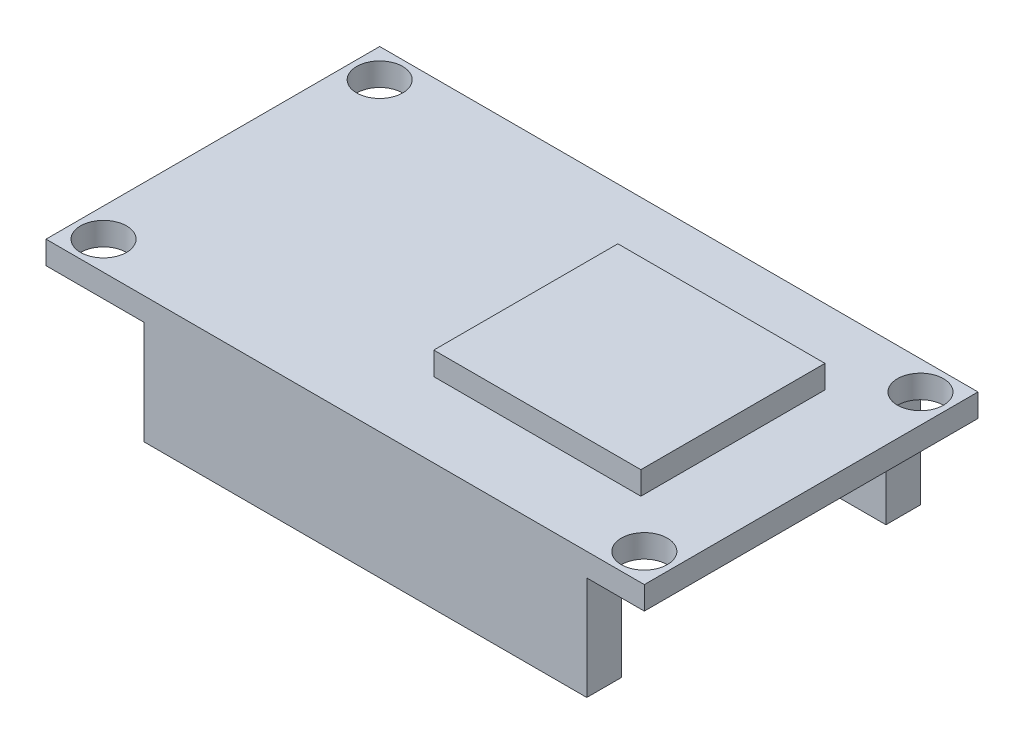
SolidWorks part; units mm, degrees
ref_plane "前视基准面" through (0, 0, 0) normal (0, 0, 1) x (1, 0, 0)
ref_plane "上视基准面" through (0, 0, 0) normal (0, 1, 0) x (1, 0, 0)
ref_plane "右视基准面" through (0, 0, 0) normal (1, 0, 0) x (0, 0, -1)
sketch "草图1" plane through (0, 0, 0) normal (0, 1, 0) x (1, 0, 0)
  line L0 (52, 14.5) -> (0, 14.5) construction
  line L1 (0, 0) -> (52, 0)
  line L2 (0, 0) -> (0, 29)
  line L3 (0, 29) -> (52, 29)
  line L4 (52, 0) -> (52, 29)
  line L5 (26, 29) -> (26, 0) construction
  circle A0 centre (49.5, 26.5) radius 2
  circle A1 centre (49.5, 2.5) radius 2
  circle A2 centre (2.5, 2.5) radius 2
  circle A3 centre (2.5, 26.5) radius 2
  dimension "D3" = 4
  dimension "D4" = 24
  dimension "D5" = 47
  dimension "D1" = 52
  dimension "D2" = 29
extrude "凸台-拉伸1" add sketch "草图1" along normal blind 2
sketch "草图2" plane through (0, 2, 0) normal (0, 1, 0) x (1, 0, 0)
  line L0 (52, 14.5) -> (0, 14.5) construction
  line L1 (52, 0) -> (52, 29) construction
  line L2 (0, 29) -> (0, 0) construction
  line L3 (45.2, 6.5) -> (45.2, 22.5)
  line L4 (45.2, 22.5) -> (27.2, 22.5)
  line L5 (27.2, 22.5) -> (27.2, 6.5)
  line L6 (45.2, 6.5) -> (27.2, 6.5)
  point P11 (27.2, 14.5)
  point P12 (45.2, 14.5)
  dimension "D1" = 6.8
  dimension "D2" = 18
  dimension "D3" = 16
extrude "凸台-拉伸2" add sketch "草图2" along normal blind 2
sketch "草图3" plane through (0, 0, 0) normal (0, -1, 0) x (1, 0, 0)
  line L0 (52, -14.5) -> (0, -14.5) construction
  line L1 (52, 0) -> (52, -29) construction
  line L2 (0, -29) -> (0, 0) construction
  line L3 (0, 0) -> (52, 0) construction
  line L4 (8.5, 0) -> (47, 0)
  line L5 (8.5, 0) -> (8.5, -3)
  line L6 (8.5, -3) -> (47, -3)
  line L7 (47, 0) -> (47, -3)
  line L8 (47, -29) -> (47, -26)
  line L9 (8.5, -26) -> (47, -26)
  line L10 (8.5, -29) -> (8.5, -26)
  line L11 (8.5, -29) -> (47, -29)
  dimension "D1" = 5
  dimension "D2" = 8.5
  dimension "D3" = 3
extrude "凸台-拉伸3" add sketch "草图3" along normal blind 9
